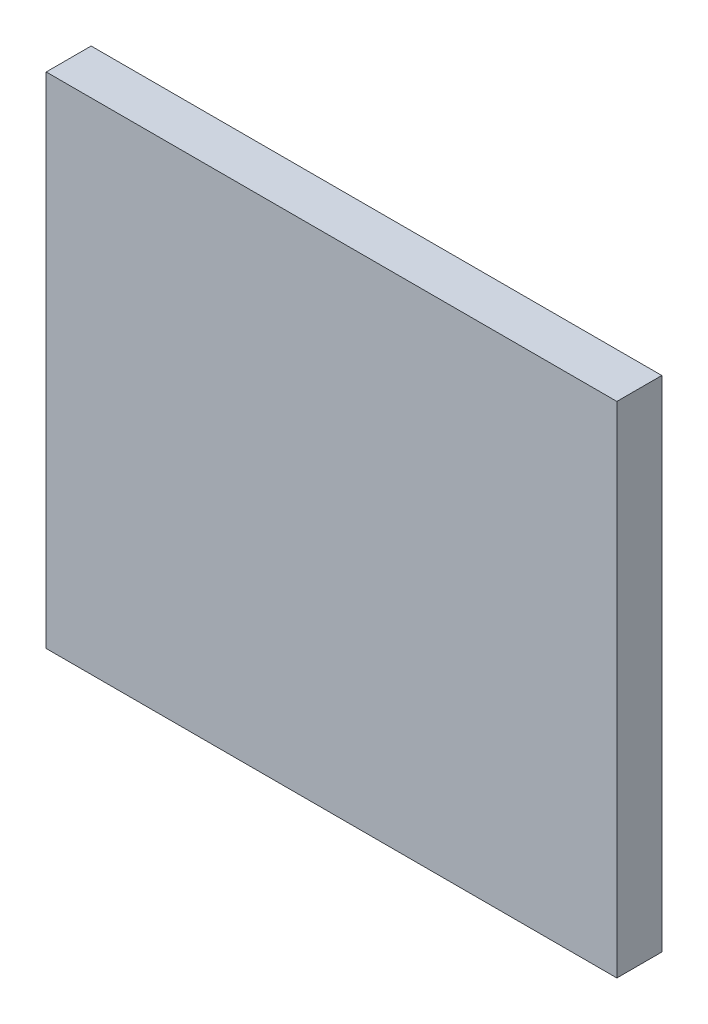
SolidWorks part; units mm, degrees
ref_plane "Front Plane" through (0, 0, 0) normal (0, 0, 1) x (1, 0, 0)
ref_plane "Top Plane" through (0, 0, 0) normal (0, 1, 0) x (1, 0, 0)
ref_plane "Right Plane" through (0, 0, 0) normal (1, 0, 0) x (0, 0, -1)
sketch "Sketch1" plane through (0, 0, 0) normal (0, 0, 1) x (1, 0, 0)
  line L0 (-10.16, 8.89) -> (-10.16, -8.89)
  line L1 (-10.16, -8.89) -> (10.16, -8.89)
  line L2 (10.16, -8.89) -> (10.16, 8.89)
  line L3 (10.16, 8.89) -> (-10.16, 8.89)
  line L5 (0, 8.89) -> (0, -8.89) construction
  line L6 (-10.16, 0) -> (10.16, 0) construction
  line L7 (55, 0) -> (-55, 0) construction
  line L8 (0, -55) -> (0, 55) construction
  dimension "D1" = 20.32
  dimension "D2" = 17.78
extrude "Boss-Extrude1" add sketch "Sketch1" along normal blind 1.6
sketch "Sketch2" plane through (0, 0, 0) normal (0, 0, 1) x (1, 0, 0)
  line L0 (5.2705, 3.683) -> (5.2705, -3.683)
  line L1 (5.2705, -3.683) -> (-5.2705, -3.683)
  line L2 (-5.2705, -3.683) -> (-5.2705, 3.683)
  line L3 (-5.2705, 3.683) -> (5.2705, 3.683)
  line L4 (5.2705, 0) -> (-5.2705, 0) construction
  line L5 (0, 3.683) -> (0, -3.683) construction
  dimension "D1" = 7.366
  dimension "D2" = 10.541
extrude "Boss-Extrude2" add sketch "Sketch2" against normal blind 3.556
